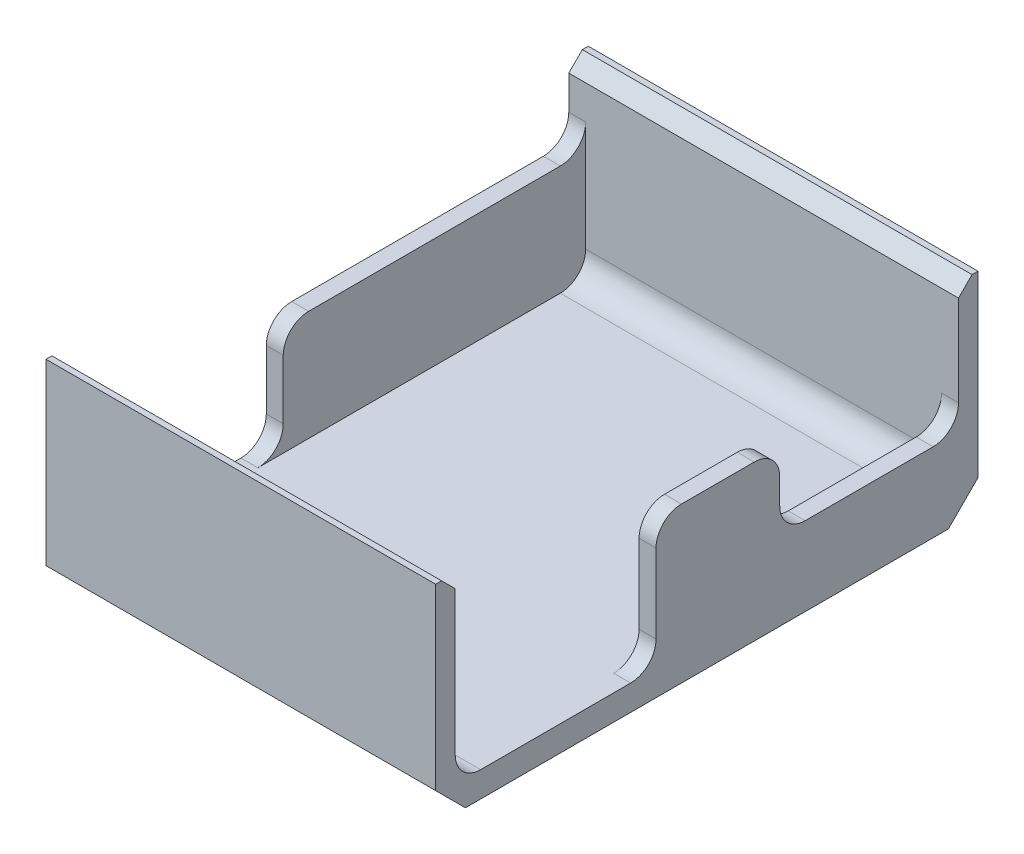
SolidWorks part; units mm, degrees
material "PETG"
ref_plane "Płaszczyzna przednia" through (0, 0, 0) normal (0, 0, 1) x (1, 0, 0)
ref_plane "Płaszczyzna górna" through (0, 0, 0) normal (0, 1, 0) x (1, 0, 0)
ref_plane "Płaszczyzna prawa" through (0, 0, 0) normal (1, 0, 0) x (0, 0, -1)
sketch "Sketch1" plane through (0, 0, 0) normal (0, 1, 0) x (1, 0, 0)
  line L1 (0, 0) -> (46, 0)
  line L2 (0, 0) -> (0, 64)
  line L3 (0, 64) -> (46, 64)
  line L4 (46, 0) -> (46, 64)
  dimension "D1" = 64
  dimension "D2" = 46
extrude "Boss-Extrude1" add sketch "Sketch1" along normal blind 3
sketch "Sketch2" plane through (0, 3, 0) normal (0, 1, 0) x (1, 0, 0)
  line L0 (46, 0) -> (46, 64) construction
  line L1 (0, 64) -> (46, 64)
  line L2 (0, 64) -> (0, 61.7)
  line L3 (0, 61.7) -> (46, 61.7)
  line L4 (46, 64) -> (46, 61.7)
  line L5 (0, 64) -> (0, 0) construction
  line L6 (46, 0) -> (0, 0)
  line L7 (46, 0) -> (46, 2.3)
  line L8 (46, 2.3) -> (0, 2.3)
  line L9 (0, 0) -> (0, 2.3)
  dimension "D1" = 2.3
  dimension "D2" = 2.3
extrude "Boss-Extrude2" add sketch "Sketch2" along normal blind 22
sketch "Sketch3" plane through (0, 0, 0) normal (-1, 0, 0) x (0, 0, 1)
  line L1 (-64, 0) -> (-26, 0)
  line L2 (-64, 0) -> (-64, 16)
  line L3 (-64, 16) -> (-26, 16)
  line L4 (-26, 0) -> (-26, 16)
  dimension "D1" = 38
  dimension "D2" = 16
extrude "Boss-Extrude3" add sketch "Sketch3" against normal blind 2
sketch "Sketch5" plane through (46, 0, 0) normal (1, 0, 0) x (0, 0, -1)
  line L1 (64, 0) -> (26, 0)
  line L2 (64, 0) -> (64, 9.3)
  line L3 (64, 9.3) -> (40.6, 9.3)
  line L4 (26, 0) -> (26, 9.3)
  line L7 (26, 9.3) -> (26, 18.3)
  line L8 (26, 18.3) -> (40.6, 18.3)
  line L9 (40.6, 9.3) -> (40.6, 18.3)
  dimension "D1" = 9.3
  dimension "D2" = 38
  dimension "D3" = 14.6
  dimension "D4" = 9
extrude "Boss-Extrude4" add sketch "Sketch5" against normal blind 2
fillet "Fillet1" radius 3 10 edges at (1, 3, -26) (1, 16, -26) (23, 3, -2.3) (1, 16, -61.7) (23, 3, -61.7) (45, 9.3, -61.7) (45, 18.3, -40.6) (45, 9.3, -40.6) (45, 3, -26) (45, 18.3, -26)
sketch "Sketch8" plane through (0, 0, 0) normal (0, -1, 0) x (1, 0, 0)
  line L0 (8.043, -38.5164) -> (8.043, 11.4665) construction
  line L2 (41.5387, -21.848) -> (41.5387, -8.8376) construction
  line L3 (41.5387, -59.1163) -> (41.5387, 5.0356) construction
  line L4 (8.043, -59.1163) -> (8.043, -43.7794) construction
  text T0 "ANTENA" font "Century Gothic" height 6
  text T1 "PC" font "Century Gothic" height 6
  text T2 "INPUT\r\n" font "Century Gothic" height 6
  text T3 "24V" font "Century Gothic" height 6
extrude "Boss-Extrude5" add sketch "Sketch8" along normal blind 0.5
chamfer "Chamfer1" distance 2 angle 45 2 edges at (23, 25, -61.7) (23, 25, -2.3)
sketch "Sketch9" plane through (0, 0, 0) normal (-1, 0, 0) x (0, 0, 1)
  line L0 (0, 25) -> (0, 0) construction
  line L1 (-64, 25) -> (0, 25)
  line L2 (-64, 25) -> (-64, 24.6)
  line L3 (-64, 24.6) -> (0, 24.6)
  line L4 (0, 25) -> (0, 24.6)
  dimension "D1" = 0.4
extrude "Cut-Extrude1" cut sketch "Sketch9" against normal through all
chamfer "Chamfer2" distance 3.5 angle 45 2 edges at (23, 0, 0) (23, 0, -64)
